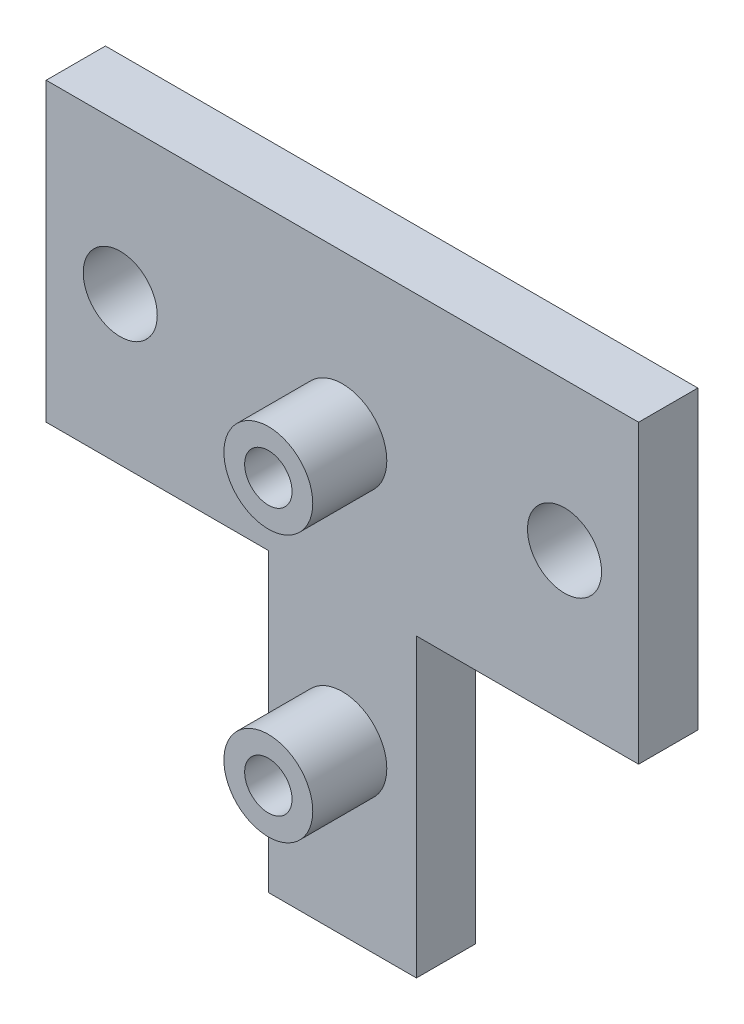
SolidWorks part; units mm, degrees
ref_plane "Front Plane" through (0, 0, 0) normal (0, 0, 1) x (1, 0, 0)
ref_plane "Top Plane" through (0, 0, 0) normal (0, 1, 0) x (1, 0, 0)
ref_plane "Right Plane" through (0, 0, 0) normal (1, 0, 0) x (0, 0, -1)
sketch "Sketch1" plane through (0, 0, 0) normal (0, 0, 1) x (1, 0, 0)
  line L0 (0, 0) -> (0, 35.2)
  line L1 (0, 0) -> (-40.2961, 0)
  line L2 (-40.2961, 0) -> (-40.2961, 35.2)
  line L3 (0, 35.2) -> (-40.2961, 35.2)
  line L4 (-20, 8.45) -> (-20, 0)
  line L5 (-20, 8.45) -> (-40.2961, 8.45)
  line L6 (-20, 26.45) -> (-40.2961, 26.45)
  line L7 (-20, 26.45) -> (-20, 35.2)
  line L8 (-20, 8.45) -> (-20, -2.8)
  line L9 (-20, -2.8) -> (-20, 37.2)
  line L11 (-25, 37.2) -> (-15, 37.2)
  line L12 (-25, 37.2) -> (-25, -2.8)
  line L13 (-25, -2.8) -> (-15, -2.8)
  line L14 (-15, 37.2) -> (-15, -2.8)
  line L15 (-40, 37.2) -> (0, 37.2)
  line L16 (-40, 37.2) -> (-40, 17.2)
  line L17 (-40, 17.2) -> (0, 17.2)
  line L18 (0, 37.2) -> (0, 17.2)
  circle A0 centre (-20, 26.45) radius 1.6
  circle A1 centre (-20, 8.45) radius 1.6
  dimension "D8" = 3.2
  dimension "D1" = 20.2961
  dimension "D2" = 8.45
  dimension "D3" = 20.2961
  dimension "D4" = 8.75
  dimension "D5" = 18
  dimension "D6" = 40.2961
  dimension "D7" = 0
  dimension "D9" = 11.25
  dimension "D10" = 40
  dimension "D11" = 40
  dimension "D12" = 10
  dimension "D13" = 5
  dimension "D14" = 20
  dimension "D15" = 0
  dimension "D16" = 20
  dimension "D17" = 40
extrude "Boss-Extrude1" add sketch "Sketch1" along normal blind 4 contours A1 L9 L1 L14 L17 | A1 L9 L17 L12 L5 | A1 L5 L12 L1 L9 | L12 L13 L8 L1 | L14 L1 L8 L13 | A0 L9 L17 L14 L3 | A0 L6 L12 L17 L9 | A0 L9 L3 L12 L6 | L14 L11 L9 L3 | L11 L12 L3 L9 | L18 L15 L14 L3 | L15 L16 L3 L12 | L3 L16 L6 L12 | L16 L17 L12 L6 | L14 L17 L0 L3
sketch "Sketch2" plane through (0, 0, 4) normal (0, 0, 1) x (1, 0, 0)
  line L0 (-5, 27.2) -> (-35, 27.2)
  line L1 (0, 17.2) -> (0, 37.2) construction
  line L2 (-40, 37.2) -> (0, 37.2) construction
  circle A0 centre (-35, 27.2) radius 2.5
  circle A1 centre (-5, 27.2) radius 2.5
  dimension "D3" = 5
  dimension "D4" = 5
  dimension "D1" = 30
  dimension "D2" = 5
  dimension "D5" = 10
extrude "Cut-Extrude1" cut sketch "Sketch2" against normal blind 13
sketch "Sketch3" plane through (0, 0, 4) normal (0, 0, 1) x (1, 0, 0)
  circle A0 centre (-20, 26.45) radius 3
  circle A1 centre (-20, 8.45) radius 3
  circle A2 centre (-20, 26.45) radius 1.6
  circle A3 centre (-20, 8.45) radius 1.6
  dimension "D1" = 6
  dimension "D2" = 6
  dimension "D3" = 3.2
  dimension "D4" = 3.2
extrude "Boss-Extrude2" add sketch "Sketch3" along normal blind 5
sketch "Sketch4" plane through (0, 0, 0) normal (0, 0, -1) x (-1, 0, 0)
  circle A0 centre (20, 26.45) radius 2.5
  circle A1 centre (20, 8.45) radius 2.5
  dimension "D1" = 5
  dimension "D2" = 5
extrude "Cut-Extrude3" cut sketch "Sketch4" against normal blind 3
